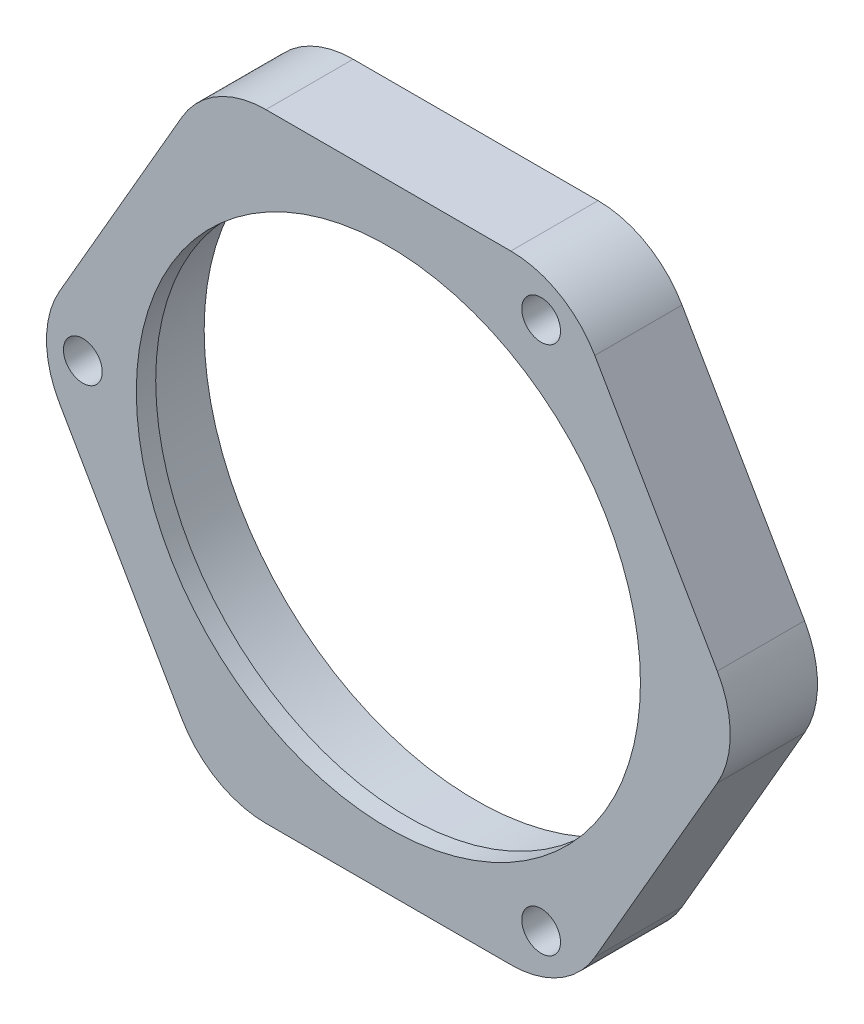
SolidWorks part; units mm, degrees
ref_plane "Front Plane" through (0, 0, 0) normal (0, 0, 1) x (1, 0, 0)
ref_plane "Top Plane" through (0, 0, 0) normal (0, 1, 0) x (1, 0, 0)
ref_plane "Right Plane" through (0, 0, 0) normal (1, 0, 0) x (0, 0, -1)
sketch "Sketch1" plane through (0, 0, 0) normal (0, 0, 1) x (1, 0, 0)
  line L1 (18.4059, -31.88) -> (36.8119, 0)
  line L2 (36.8119, 0) -> (18.4059, 31.88)
  line L3 (18.4059, 31.88) -> (-18.4059, 31.88)
  line L4 (-18.4059, 31.88) -> (-36.8119, 0)
  line L5 (-36.8119, 0) -> (-18.4059, -31.88)
  line L6 (-18.4059, -31.88) -> (18.4059, -31.88)
  circle A0 centre (0, 0) radius 28
  circle A1 centre (0, 0) radius 31.88 construction
  dimension "D1" = 63.76
  dimension "D2" = 56
extrude "Boss-Extrude1" add sketch "Sketch1" along normal blind 9
fillet "Fillet1" radius 10 6 edges at (-18.4059, -31.88, 4.5) (18.4059, -31.88, 4.5) (-36.8119, 0, 4.5) (36.8119, 0, 4.5) (18.4059, 31.88, 4.5) (-18.4059, 31.88, 4.5)
sketch "Sketch3" plane through (0, 0, 9) normal (0, 0, 1) x (1, 0, 0)
  line L0 (0, 0) -> (-35.2648, 0) construction
  arc A0 (-33.9251, 5) -> (-33.9251, -5) centre (-25.2648, 0) ccw construction
  circle A1 centre (-31.5148, 0) radius 3.75 construction
  circle A2 centre (-31.5148, 0) radius 2
  dimension "D1" = 7.5
  dimension "D2" = 4
extrude "Cut-Extrude1" cut sketch "Sketch3" against normal through all contours A2
pattern_circular "CirPattern1" count 3 over 360 about axis through (0, 0, 0) along (0, 0, 1) of "Cut-Extrude1"
sketch "Sketch4" plane through (0, 0, 9) normal (0, 0, 1) x (1, 0, 0)
  circle A0 centre (0, 0) radius 28 construction
  circle A1 centre (0, 0) radius 28
  circle A2 centre (0, 0) radius 26
  dimension "D1" = 2
extrude "Boss-Extrude2" add sketch "Sketch4" against normal blind 2
equation "\"Depth\"= 9mm"
equation "\"de\"=5"
equation "\"D1@Boss-Extrude1\"=\"Depth\""
